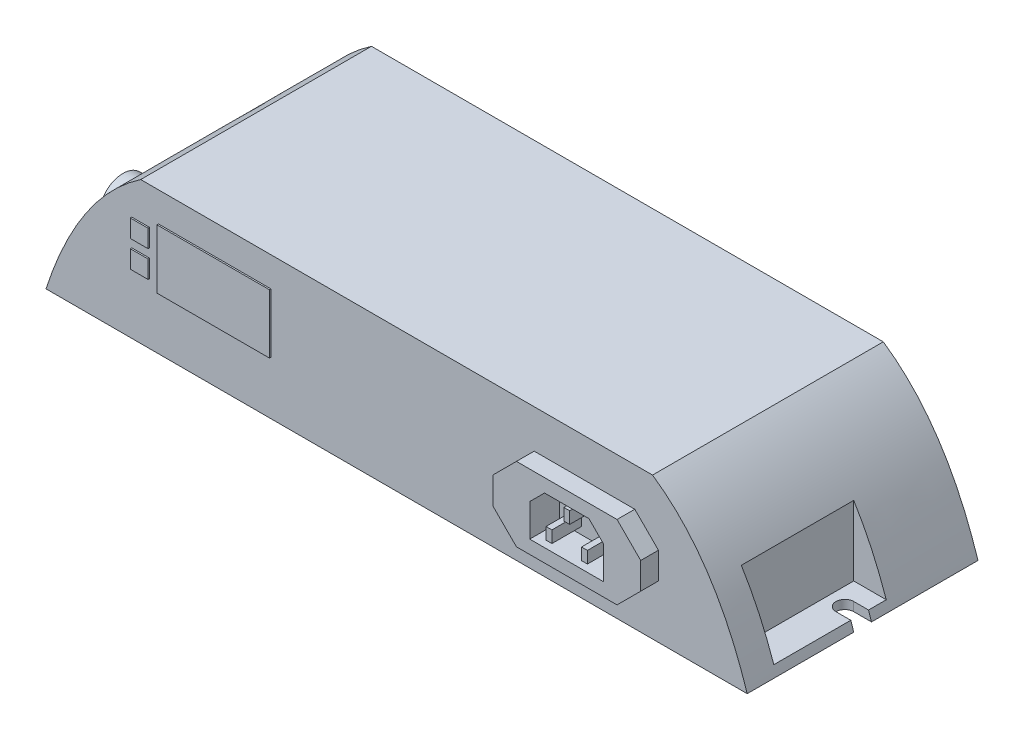
SolidWorks part; units mm, degrees
ref_plane "Front Plane" through (0, 0, 0) normal (0, 0, 1) x (1, 0, 0)
ref_plane "Top Plane" through (0, 0, 0) normal (0, 1, 0) x (1, 0, 0)
ref_plane "Right Plane" through (0, 0, 0) normal (1, 0, 0) x (0, 0, -1)
sketch "Sketch1" plane through (0, 0, 0) normal (0, 1, 0) x (1, 0, 0)
  line L1 (-118.5, -39) -> (118.5, -39)
  line L2 (-118.5, -39) -> (-118.5, 39)
  line L3 (-118.5, 39) -> (118.5, 39)
  line L4 (118.5, -39) -> (118.5, 39)
  line L5 (-118.5, -39) -> (118.5, 39) construction
  line L6 (-118.5, 39) -> (118.5, -39) construction
  point P0 (0, 0)
  dimension "D1" = 237
  dimension "D2" = 78
extrude "Boss-Extrude1" add sketch "Sketch1" along normal blind 48
sketch "Sketch2" plane through (118.5, 0, 0) normal (1, 0, 0) x (0, 0, -1)
  line L0 (0, 48) -> (0, 0) construction
  line L1 (-39, 48) -> (39, 48) construction
  line L2 (-39, 0) -> (39, 0) construction
  line L3 (-29, 3) -> (9, 3)
  line L4 (-29, 3) -> (-29, 33)
  line L5 (-29, 33) -> (9, 33)
  line L6 (9, 3) -> (9, 33)
  line L7 (-29, 3) -> (9, 33) construction
  line L8 (-29, 33) -> (9, 3) construction
  line L9 (-39, 48) -> (-39, 0) construction
  point P4 (-10, 18)
  dimension "D1" = 3
  dimension "D2" = 38
  dimension "D3" = 10
  dimension "D4" = 30
extrude "Cut-Extrude1" cut sketch "Sketch2" against normal blind 12
sketch "Sketch3" plane through (0, 0, 39) normal (0, 0, 1) x (1, 0, 0)
  line L0 (0, 48) -> (0, 0) construction
  line L1 (-118.5, 48) -> (118.5, 48) construction
  line L2 (86.5, 48) -> (86.5, 0) construction
  line L3 (-118.5, 0) -> (118.5, 0) construction
  line L4 (118.5, 48) -> (118.5, 0) construction
  line L5 (118.5, 0) -> (133.8184, 0)
  line L6 (133.8184, 0) -> (133.8184, 98.6767)
  line L7 (133.8184, 98.6767) -> (0, 98.6767)
  line L8 (0, 98.6767) -> (0, 48)
  spline S0 degree 2 poles (118.5, 0) (91.3536, 83.9862) (0, 48) knots 0 0 0 1 1 1
  dimension "D1" = 32
extrude "Cut-Extrude2" cut sketch "Sketch3" against normal through all
mirror "Mirror1" about plane through (0, 0, 0) normal (1, 0, 0) of "Cut-Extrude2", "Cut-Extrude1"
sketch "Sketch4" plane through (-106.5, 0, 0) normal (1, 0, 0) x (0, 0, -1)
  line L0 (-29, 3) -> (9, 26.5841) construction
  line L2 (-29, 3) -> (-29, 26.5841) construction
  circle A0 centre (-15, 14.792) radius 8
  dimension "D1" = 16
  dimension "D2" = 14
extrude "Boss-Extrude2" add sketch "Sketch4" against normal blind 10
sketch "Sketch5" plane through (0, 0, 39) normal (0, 0, 1) x (1, 0, 0)
  line L0 (0, 0) -> (0, 48) construction
  line L1 (-118.5, 0) -> (118.5, 0) construction
  line L2 (-86.5, 48) -> (86.5, 48) construction
  line L3 (0, 24) -> (108.0561, 24) construction
  line L4 (46.5, 35) -> (38.5, 27)
  line L5 (80.5, 10) -> (46.5, 10)
  line L6 (88.5, 18) -> (88.5, 27)
  line L7 (80.5, 35) -> (46.5, 35)
  line L8 (38.5, 18) -> (38.5, 27)
  line L9 (88.5, 10) -> (38.5, 35) construction
  line L10 (88.5, 35) -> (38.5, 10) construction
  line L11 (46.5, 10) -> (38.5, 18)
  line L12 (88.5, 27) -> (80.5, 35)
  line L13 (88.5, 18) -> (80.5, 10)
  parabola Q0 (86.5, 48) -> (118.5, 0) focus (67.0505, 25.1168) apex (81.0611, 51.2959) construction
  point P12 (63.5, 22.5)
  dimension "D1" = 10
  dimension "D2" = 30
  dimension "D3" = 50
  dimension "D4" = 25
extrude "Boss-Extrude3" add sketch "Sketch5" along normal blind 6
sketch "Sketch6" plane through (0, 0, 45) normal (0, 0, 1) x (1, 0, 0)
  line L0 (46.5, 35) -> (80.5, 10) construction
  line L1 (51, 25.5) -> (56, 30.5)
  line L2 (51, 14.5) -> (76, 14.5)
  line L3 (51, 14.5) -> (51, 25.5)
  line L4 (56, 30.5) -> (71, 30.5)
  line L5 (76, 14.5) -> (76, 25.5)
  line L6 (51, 14.5) -> (76, 30.5) construction
  line L7 (51, 30.5) -> (76, 14.5) construction
  line L8 (71, 30.5) -> (76, 25.5)
  line L9 (80.5, 35) -> (46.5, 35) construction
  line L10 (46.5, 35) -> (38.5, 27) construction
  line L11 (46.5, 10) -> (80.5, 10) construction
  line L12 (88.5, 22.5) -> (38.5, 22.5) construction
  line L13 (88.5, 18) -> (88.5, 27) construction
  line L14 (38.5, 27) -> (38.5, 18) construction
  point P4 (63.5, 22.5)
  dimension "D1" = 25
  dimension "D2" = 16
extrude "Cut-Extrude3" cut sketch "Sketch6" against normal blind 10
sketch "Sketch7" plane through (0, 0, 35) normal (0, 0, 1) x (1, 0, 0)
  line L0 (63.5, 30.5) -> (63.5, 14.5) construction
  line L1 (71, 30.5) -> (56, 30.5) construction
  line L2 (51, 14.5) -> (76, 14.5) construction
  line L3 (70.5, 16.9509) -> (68.5, 20.9509) construction
  line L4 (62.5, 29.5497) -> (64.5, 29.5497)
  line L5 (62.5, 29.5497) -> (62.5, 25.5497)
  line L6 (62.5, 25.5497) -> (64.5, 25.5497)
  line L7 (64.5, 29.5497) -> (64.5, 25.5497)
  line L8 (62.5, 29.5497) -> (64.5, 25.5497) construction
  line L9 (62.5, 25.5497) -> (64.5, 29.5497) construction
  line L10 (56.5, 20.9509) -> (58.5, 20.9509)
  line L11 (56.5, 20.9509) -> (56.5, 16.9509)
  line L12 (56.5, 16.9509) -> (58.5, 16.9509)
  line L13 (58.5, 20.9509) -> (58.5, 16.9509)
  line L14 (56.5, 20.9509) -> (58.5, 16.9509) construction
  line L15 (56.5, 16.9509) -> (58.5, 20.9509) construction
  line L16 (70.5, 20.9509) -> (68.5, 16.9509) construction
  line L17 (68.5, 20.9509) -> (68.5, 16.9509)
  line L18 (70.5, 16.9509) -> (68.5, 16.9509)
  line L19 (70.5, 20.9509) -> (70.5, 16.9509)
  line L20 (70.5, 20.9509) -> (68.5, 20.9509)
  point P6 (63.5, 27.5497)
  point P11 (57.5, 18.9509)
  point P20 (69.5, 18.9509)
  dimension "D1" = 6
  dimension "D2" = 2
  dimension "D3" = 4
extrude "Boss-Extrude4" add sketch "Sketch7" along normal up to surface (10 mm away) up to face at (63.5, 23.5, 45)
sketch "Sketch8" plane through (0, 0, 39) normal (0, 0, 1) x (1, 0, 0)
  line L0 (-118.5, 0) -> (118.5, 0) construction
  line L1 (-80.5, 38) -> (-42.5, 38)
  line L2 (-80.5, 38) -> (-80.5, 18)
  line L3 (-80.5, 18) -> (-42.5, 18)
  line L4 (-42.5, 38) -> (-42.5, 18)
  line L5 (-80.5, 38) -> (-42.5, 18) construction
  line L6 (-80.5, 18) -> (-42.5, 38) construction
  line L7 (-42.5, 28) -> (-80.5, 28) construction
  line L8 (-89.5, 35.5) -> (-83.5, 29.5) construction
  line L9 (-89.5, 26.5) -> (-83.5, 26.5)
  line L10 (-89.5, 26.5) -> (-89.5, 20.5)
  line L11 (-89.5, 20.5) -> (-83.5, 20.5)
  line L12 (-83.5, 26.5) -> (-83.5, 20.5)
  line L13 (-89.5, 26.5) -> (-83.5, 20.5) construction
  line L14 (-89.5, 20.5) -> (-83.5, 26.5) construction
  line L15 (-89.5, 29.5) -> (-83.5, 35.5) construction
  line L16 (-83.5, 29.5) -> (-83.5, 35.5)
  line L17 (-89.5, 35.5) -> (-83.5, 35.5)
  line L18 (-89.5, 29.5) -> (-89.5, 35.5)
  line L19 (-89.5, 29.5) -> (-83.5, 29.5)
  point P0 (-61.5, 28)
  point P10 (-86.5, 23.5)
  point P19 (-86.5, 32.5)
  dimension "D1" = 38
  dimension "D2" = 20
  dimension "D3" = 38
  dimension "D4" = 18
  dimension "D5" = 6
  dimension "D6" = 6
  dimension "D7" = 3
  dimension "D8" = 3
extrude "Boss-Extrude5" add sketch "Sketch8" along normal blind 0.5
sketch "Sketch9" plane through (0, 0, 0) normal (0, -1, 0) x (1, 0, 0)
  line L0 (-118.5, 0) -> (118.5, 0) construction
  line L1 (-118.5, -39) -> (-118.5, 39) construction
  line L2 (118.5, 39) -> (118.5, -39) construction
  line L3 (-112.5, -3) -> (-118.5, -3)
  line L4 (-112.5, 3) -> (-118.5, 3)
  line L5 (-118.5, 3) -> (-118.5, -3)
  line L6 (0, -39) -> (0, 39) construction
  line L7 (86.5, -39) -> (-86.5, -39) construction
  line L8 (-86.5, 39) -> (86.5, 39) construction
  line L9 (118.5, 3) -> (118.5, -3)
  line L10 (112.5, 3) -> (118.5, 3)
  line L11 (112.5, -3) -> (118.5, -3)
  arc A0 (-112.5, -3) -> (-112.5, 3) centre (-112.5, 0) ccw
  arc A1 (112.5, -3) -> (112.5, 3) centre (112.5, 0) cw
  point P8 (0, 0)
  dimension "D1" = 112.5
  dimension "D2" = 6
extrude "Cut-Extrude4" cut sketch "Sketch9" against normal through all
